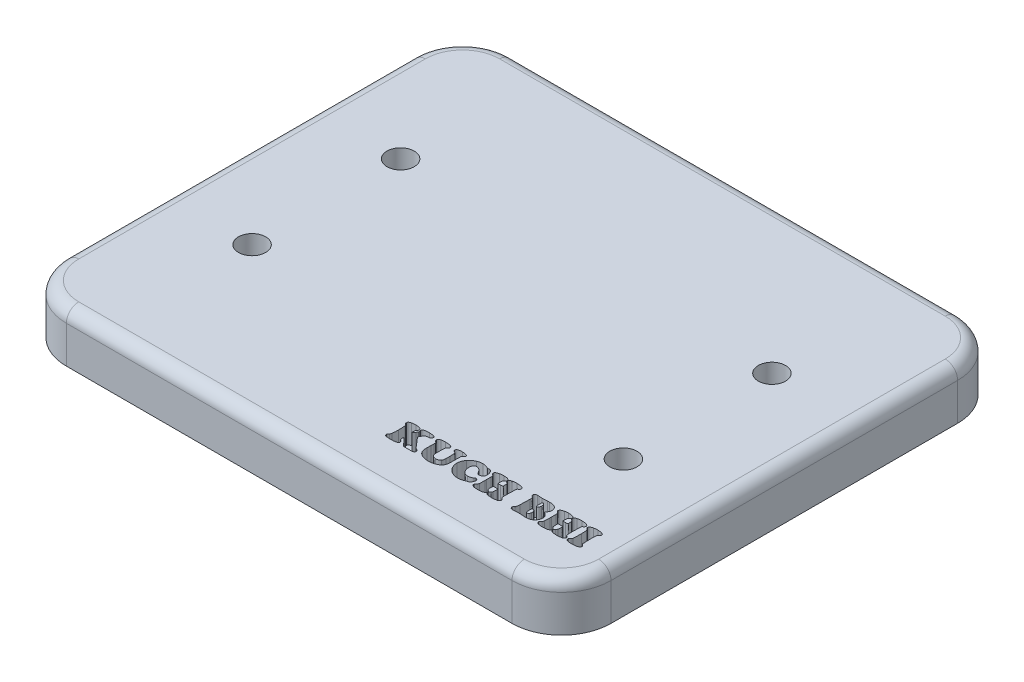
SolidWorks part; units mm, degrees
ref_plane "Front Plane" through (0, 0, 0) normal (0, 0, 1) x (1, 0, 0)
ref_plane "Top Plane" through (0, 0, 0) normal (0, 1, 0) x (1, 0, 0)
ref_plane "Right Plane" through (0, 0, 0) normal (1, 0, 0) x (0, 0, -1)
sketch "Sketch1" plane through (0, 0, 0) normal (0, 1, 0) x (1, 0, 0)
  line L1 (-90, 90) -> (90, 90)
  line L2 (-110, 70) -> (-110, -70)
  line L3 (-90, -90) -> (90, -90)
  line L4 (110, 70) -> (110, -70)
  line L5 (-110, 90) -> (110, -90) construction
  line L6 (-110, -90) -> (110, 90) construction
  arc A0 (90, 90) -> (110, 70) centre (90, 70) cw
  arc A1 (-110, -70) -> (-90, -90) centre (-90, -70) ccw
  arc A2 (-90, 90) -> (-110, 70) centre (-90, 70) ccw
  arc A3 (90, -90) -> (110, -70) centre (90, -70) ccw
  point P0 (0, 0)
  dimension "D3" = 20
  dimension "D1" = 220
  dimension "D2" = 180
extrude "Boss-Extrude1" add sketch "Sketch1" along normal blind 20
fillet "Fillet1" radius 5 8 edges at (110, 20, 0) (104.1421, 20, 84.1421) (0, 20, 90) (-104.1421, 20, 84.1421) (-110, 20, 0) (-104.1421, 20, -84.1421) (0, 20, -90) (104.1421, 20, -84.1421)
sketch "Sketch2" plane through (0, 20, 0) normal (0, 1, 0) x (1, 0, 0)
  line L0 (-11, 0) -> (11, 0) construction
  circle A0 centre (-75, 30) radius 5.5
  circle A1 centre (75, 30) radius 5.5
  dimension "D1" = 30
  dimension "D4" = 11
  dimension "D5" = 11
  dimension "D2" = 75
  dimension "D3" = 75
extrude "Cut-Extrude1" cut sketch "Sketch2" against normal through all
sketch "Sketch3" plane through (0, 0, 0) normal (0, -1, 0) x (1, 0, 0)
  circle A0 centre (-75, -30) radius 9
  circle A1 centre (75, -30) radius 9
  dimension "D1" = 18
  dimension "D2" = 18
extrude "Cut-Extrude2" cut sketch "Sketch3" against normal blind 11
mirror "Mirror1" about plane through (0, 0, 0) normal (0, 0, 1) of "Cut-Extrude2", "Cut-Extrude1"
sketch "Sketch4" plane through (0, 20, 0) normal (0, 1, 0) x (1, 0, 0)
  text T0 "<b>KUCH BHI </b>" font "Cooper Black" height 10
extrude "Cut-Extrude3" cut sketch "Sketch4" against normal blind 8
